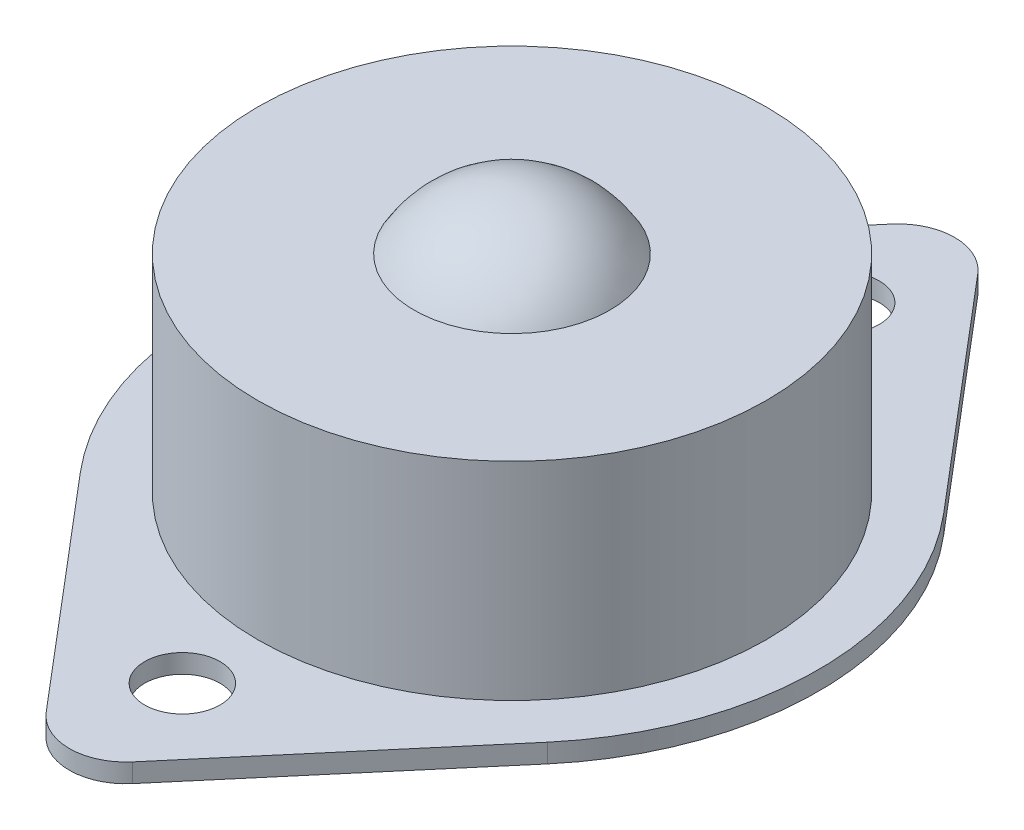
SolidWorks part; units mm, degrees
ref_plane "前视基准面" through (0, 0, 0) normal (0, 0, 1) x (1, 0, 0)
ref_plane "上视基准面" through (0, 0, 0) normal (0, 1, 0) x (1, 0, 0)
ref_plane "右视基准面" through (0, 0, 0) normal (1, 0, 0) x (0, 0, -1)
sketch "草图1" plane through (0, 0, 0) normal (1, 0, 0) x (0, 0, -1)
  line L0 (0, 0) -> (-23.5, 0)
  line L1 (-23.5, 0) -> (-23.5, 1)
  line L2 (-23.5, 1) -> (-13.5, 1)
  line L3 (-13.5, 1) -> (-13.5, 12)
  line L4 (-13.5, 12) -> (-5.1962, 12)
  line L7 (0, 0) -> (0, 9)
  line L8 (0, 9) -> (0, 15)
  arc A2 (0, 15) -> (-5.1962, 12) centre (0, 9) ccw
  point P9 (-5.1738, 12.0384)
  dimension "D1" = 23.5
  dimension "D2" = 1
  dimension "D3" = 10
  dimension "D4" = 11
  dimension "D5" = 15
  dimension "D6" = 9
  dimension "D7" = 6
sketch "草图3" plane through (0, 0, 0) normal (0, 1, 0) x (1, 0, 0)
  line L1 (0, 0) -> (0, -23.5) construction
  circle A0 centre (0, 17.5) radius 2
  circle A1 centre (0, -17.5) radius 2
revolve "旋转2" add sketch "草图1" angle 360 about L7
extrude "切除-拉伸4" cut sketch "草图3" along normal up to surface (1 mm away) up to face at (0, 1, -23.5)
sketch "草图4" plane through (0, 0, 0) normal (0, 1, 0) x (1, 0, 0)
  line L0 (0, 16.259) -> (0, -25.0137) construction
  line L1 (2.288, 22.4403) -> (12.4004, 10.516)
  line L2 (-2.288, 22.4403) -> (-12.4004, 10.516)
  line L3 (2.288, -22.4403) -> (12.4004, -10.516)
  line L4 (-12.4004, -10.516) -> (-2.288, -22.4403)
  arc A0 (-12.4004, 10.516) -> (-12.4004, -10.516) centre (0, 0) ccw
  arc A1 (2.288, 22.4403) -> (-2.288, 22.4403) centre (0, 20.5) ccw
  arc A2 (-2.288, -22.4403) -> (2.288, -22.4403) centre (0, -20.5) ccw
  circle A3 centre (0, 0) radius 23.5 construction
  arc A4 (12.4004, -10.516) -> (12.4004, 10.516) centre (0, 0) ccw
sketch "草图5" plane through (0, 0, 0) normal (0, 1, 0) x (1, 0, 0)
  line L4 (2.288, -22.4403) -> (12.4004, -10.516)
  line L5 (-12.4004, -10.516) -> (-2.288, -22.4403)
  line L6 (-2.288, 22.4403) -> (-12.4004, 10.516)
  line L7 (12.4004, 10.516) -> (2.288, 22.4403)
  line L8 (2.288, -22.4403) -> (12.4004, -10.516)
  line L9 (-12.4004, -10.516) -> (-2.288, -22.4403)
  line L10 (-2.288, 22.4403) -> (-12.4004, 10.516)
  line L11 (12.4004, 10.516) -> (2.288, 22.4403)
  circle A0 centre (0, 0) radius 33.3062
  arc A4 (-2.288, -22.4403) -> (2.288, -22.4403) centre (0, -20.5) ccw
  arc A5 (-12.4004, 10.516) -> (-12.4004, -10.516) centre (0, 0) ccw
  arc A6 (2.288, 22.4403) -> (-2.288, 22.4403) centre (0, 20.5) ccw
  arc A7 (12.4004, -10.516) -> (12.4004, 10.516) centre (0, 0) ccw
  arc A8 (-2.288, -22.4403) -> (2.288, -22.4403) centre (0, -20.5) ccw
  arc A9 (-12.4004, 10.516) -> (-12.4004, -10.516) centre (0, 0) ccw
  arc A10 (2.288, 22.4403) -> (-2.288, 22.4403) centre (0, 20.5) ccw
  arc A11 (12.4004, -10.516) -> (12.4004, 10.516) centre (0, 0) ccw
  dimension "D1" = 0
extrude "切除-拉伸5" cut sketch "草图5" along normal up to surface (1 mm away) up to face at (0, 1, -19.5)
